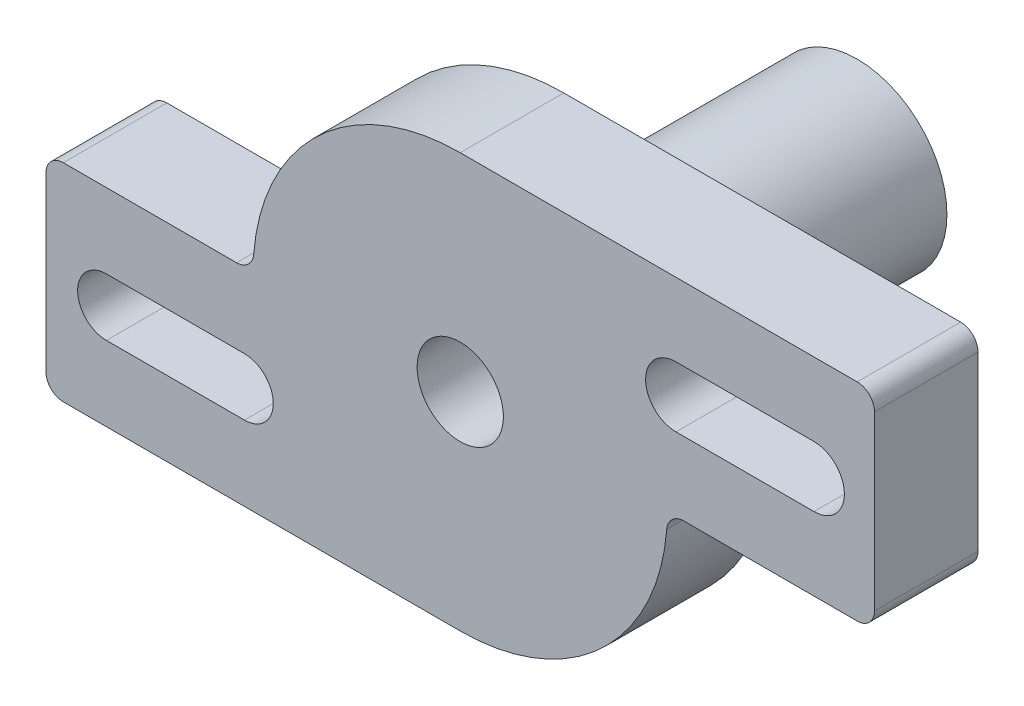
SolidWorks part; units mm, degrees
ref_plane "Front Plane" through (0, 0, 0) normal (0, 0, 1) x (1, 0, 0)
ref_plane "Top Plane" through (0, 0, 0) normal (0, 1, 0) x (1, 0, 0)
ref_plane "Right Plane" through (0, 0, 0) normal (1, 0, 0) x (0, 0, -1)
sketch "Sketch1" plane through (0, 0, 0) normal (0, 0, 1) x (1, 0, 0)
  line L0 (-37.5398, 91.3957) -> (-41.5398, 91.3957) construction
  line L3 (-37.5398, 90.5167) -> (-41.5398, 90.5167)
  line L4 (-47.7898, 94.3957) -> (-35.7898, 94.3957)
  line L5 (-59.7898, 82.3957) -> (-47.7898, 82.3957)
  line L6 (-53.7898, 88.3957) -> (-59.7898, 88.3957)
  line L7 (-41.7898, 88.3957) -> (-35.7898, 88.3957)
  line L8 (-59.7898, 88.3957) -> (-59.7898, 82.3957)
  line L9 (-35.7898, 94.3957) -> (-35.7898, 88.3957)
  line L10 (-37.5398, 92.2746) -> (-41.5398, 92.2746)
  line L11 (-58.0398, 85.3957) -> (-54.0398, 85.3957) construction
  line L12 (-58.0398, 86.2297) -> (-54.0398, 86.2297)
  line L13 (-58.0398, 84.5616) -> (-54.0398, 84.5616)
  arc A1 (-37.5398, 90.5167) -> (-37.5398, 92.2746) centre (-37.5398, 91.3957) ccw
  arc A2 (-47.7898, 94.3957) -> (-53.7898, 88.3957) centre (-47.7898, 88.3957) ccw
  arc A3 (-47.7898, 82.3957) -> (-41.7898, 88.3957) centre (-47.7898, 88.3957) ccw
  arc A4 (-41.5398, 92.2746) -> (-41.5398, 90.5167) centre (-41.5398, 91.3957) ccw
  arc A5 (-58.0398, 86.2297) -> (-58.0398, 84.5616) centre (-58.0398, 85.3957) ccw
  arc A6 (-54.0398, 84.5616) -> (-54.0398, 86.2297) centre (-54.0398, 85.3957) ccw
  point P7 (-39.5398, 91.3957)
  point P16 (-56.0398, 85.3957)
  dimension "D3" = 6
  dimension "D1" = 12
  dimension "D2" = 12
  dimension "D4" = 6
  dimension "D5" = 6
  dimension "D6" = 4
  dimension "D7" = 4
  dimension "D8" = 6.25
  dimension "D9" = 6.25
  dimension "D10" = 3
  dimension "D11" = 3
extrude "Boss-Extrude1" add sketch "Sketch1" along normal blind 3
sketch "Sketch2" plane through (0, 0, 0) normal (0, 0, -1) x (-1, 0, 0)
  circle A0 centre (47.7898, 88.3957) radius 2.6
  dimension "D1" = 5.2
extrude "Boss-Extrude2" add sketch "Sketch2" along normal blind 8.5
hole_wizard "M3 Tapped Hole1" positions "Sketch5" profile "Sketch3" tap size "M3" standard "DIN" end condition through all
sketch "Sketch5" plane through (0, 0, -8.5) normal (0, 0, -1) x (-1, 0, 0)
  point P0 (47.7898, 88.3957)
cosmetic thread "Hole Thread1" parameters "D2"=3
sketch "Sketch3" plane through (-47.7898, 88.3957, -8.5) normal (1, 0, 0) x (0, 1, 0)
  line L0 (0, 0) -> (0, 11.5)
  line L1 (0, 11.5) -> (1.25, 11.5)
  line L2 (1.25, 11.5) -> (1.25, 0)
  line L5 (1.25, 0) -> (0, 0)
  line L11 (0, -6.35) -> (0, 107.95) construction
  dimension "Thru Tap Drill Dia." = 2.5
  dimension "Thru Tap Drill Depth" = 11.5
fillet "Fillet1" radius 0.5 7 edges at (-45.1898, 88.3957, 0) (-59.7898, 82.3957, 1.5) (-59.7898, 88.3957, 1.5) (-53.7898, 88.3957, 1.5) (-41.7898, 88.3957, 1.5) (-35.7898, 88.3957, 1.5) (-35.7898, 94.3957, 1.5)
